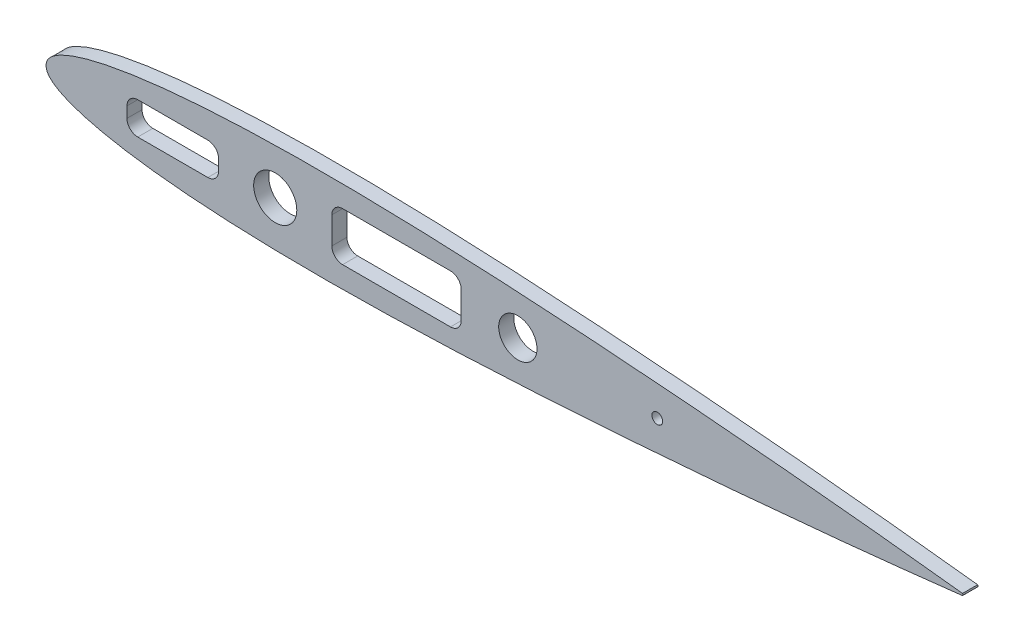
SolidWorks part; units mm, degrees
material "Фанера"
ref_plane "Front Plane" through (0, 0, 0) normal (0, 0, 1) x (1, 0, 0)
ref_plane "Top Plane" through (0, 0, 0) normal (0, 1, 0) x (1, 0, 0)
ref_plane "Right Plane" through (0, 0, 0) normal (1, 0, 0) x (0, 0, -1)
curve "Кривая1"
  spline degree 3 poles (110, 0, 0) (110.0276, -0.2367, 0) (110.0855, -0.7342, 0) (110.5302, -1.4271, 0) (111.1963, -2.0786, 0) (112.1098, -2.7013, 0) (113.2568, -3.2993, 0) (114.6379, -3.8731, 0) (116.2477, -4.4214, 0) (118.0813, -4.9426, 0) (120.1331, -5.4348, 0) (122.3972, -5.8961, 0) (124.8672, -6.3247, 0) (127.537, -6.7187, 0) (130.3997, -7.0764, 0) (133.4488, -7.3965, 0) (136.6771, -7.6776, 0) (140.0777, -7.9187, 0) (143.6433, -8.119, 0) (147.3662, -8.278, 0) (151.2389, -8.3955, 0) (155.2534, -8.4715, 0) (159.4016, -8.5065, 0) (163.6751, -8.501, 0) (168.0653, -8.456, 0) (172.5632, -8.3725, 0) (177.1595, -8.252, 0) (181.8446, -8.096, 0) (186.6087, -7.9062, 0) (191.4413, -7.6846, 0) (196.3316, -7.4331, 0) (201.2684, -7.1538, 0) (206.2396, -6.8489, 0) (211.233, -6.5205, 0) (216.2352, -6.1709, 0) (221.2323, -5.8022, 0) (226.2093, -5.417, 0) (231.1504, -5.0174, 0) (236.0382, -4.6058, 0) (240.8542, -4.1849, 0) (245.5777, -3.7574, 0) (250.1862, -3.3262, 0) (254.6542, -2.8948, 0) (258.9526, -2.4672, 0) (263.0477, -2.0479, 0) (266.899, -1.6426, 0) (270.4558, -1.2586, 0) (273.6512, -0.9053, 0) (276.3854, -0.5964, 0) (278.4526, -0.359, 0) (279.592, -0.2261, 0) (280, -0.1785, 0) knots 0 0 0 0 0.004099 0.008615 0.013935 0.020278 0.027753 0.03641 0.046266 0.05732 0.069559 0.082963 0.097507 0.113164 0.129903 0.14769 0.166492 0.186272 0.206992 0.228612 0.251092 0.274389 0.298458 0.323254 0.348728 0.37483 0.401509 0.42871 0.456376 0.484448 0.512864 0.541558 0.570462 0.599504 0.628607 0.65769 0.686667 0.715445 0.743924 0.771995 0.79954 0.826428 0.852512 0.877624 0.901571 0.924121 0.944989 0.963804 0.980044 0.992855 1 1 1 1
curve "Кривая2"
  spline degree 3 poles (280, 0.1785, 0) (279.592, 0.2261, 0) (278.4526, 0.359, 0) (276.3854, 0.5964, 0) (273.6512, 0.9053, 0) (270.4558, 1.2586, 0) (266.899, 1.6426, 0) (263.0477, 2.0479, 0) (258.9526, 2.4672, 0) (254.6542, 2.8948, 0) (250.1862, 3.3262, 0) (245.5777, 3.7574, 0) (240.8542, 4.1849, 0) (236.0382, 4.6058, 0) (231.1504, 5.0174, 0) (226.2093, 5.417, 0) (221.2323, 5.8022, 0) (216.2352, 6.1709, 0) (211.233, 6.5205, 0) (206.2396, 6.8489, 0) (201.2684, 7.1538, 0) (196.3316, 7.4331, 0) (191.4413, 7.6846, 0) (186.6087, 7.9062, 0) (181.8446, 8.096, 0) (177.1595, 8.252, 0) (172.5632, 8.3725, 0) (168.0653, 8.456, 0) (163.6751, 8.501, 0) (159.4016, 8.5065, 0) (155.2534, 8.4715, 0) (151.2389, 8.3955, 0) (147.3662, 8.278, 0) (143.6433, 8.119, 0) (140.0777, 7.9187, 0) (136.6771, 7.6776, 0) (133.4488, 7.3965, 0) (130.3997, 7.0764, 0) (127.537, 6.7187, 0) (124.8672, 6.3247, 0) (122.3972, 5.8961, 0) (120.1331, 5.4348, 0) (118.0813, 4.9426, 0) (116.2477, 4.4214, 0) (114.6379, 3.8731, 0) (113.2568, 3.2993, 0) (112.1098, 2.7013, 0) (111.1963, 2.0786, 0) (110.5302, 1.4271, 0) (110.0855, 0.7342, 0) (110.0276, 0.2367, 0) (110, 0, 0) knots 0 0 0 0 0.007145 0.019956 0.036196 0.055011 0.075879 0.098429 0.122376 0.147488 0.173572 0.20046 0.228005 0.256076 0.284555 0.313333 0.34231 0.371393 0.400496 0.429538 0.458442 0.487136 0.515552 0.543624 0.57129 0.598491 0.62517 0.651272 0.676746 0.701542 0.725611 0.748908 0.771388 0.793008 0.813728 0.833508 0.85231 0.870097 0.886836 0.902493 0.917037 0.930441 0.94268 0.953734 0.96359 0.972247 0.979722 0.986065 0.991385 0.995901 1 1 1 1
sketch "Эскиз1" plane through (0, 0, 0) normal (0, 0, 1) x (1, 0, 0)
  line L0 (105.1708, 0) -> (280.7263, 0) construction
  line L1 (280.0739, 0) -> (280.0739, 24.3846) construction
  line L2 (110, -5.3315) -> (110, 17.5304) construction
  line L3 (152.5185, 18.8331) -> (152.5185, -21.3473) construction
  line L4 (223.3826, 13.2402) -> (223.3826, -18.4275) construction
  line L5 (217.7476, 6.0581) -> (217.7476, -6.0581)
  line L6 (127.0185, -3) -> (140.0185, -3)
  line L7 (125.0185, -1) -> (125.0185, 1)
  line L8 (127.0185, 3) -> (140.0185, 3)
  line L9 (142.0185, -1) -> (142.0185, 1)
  line L10 (125.0185, -3) -> (142.0185, 3) construction
  line L11 (125.0185, 3) -> (142.0185, -3) construction
  line L12 (165.0185, -4.5) -> (185.0185, -4.5)
  line L13 (163.0185, -2.5) -> (163.0185, 2.5)
  line L14 (165.0185, 4.5) -> (185.0185, 4.5)
  line L15 (187.0185, -2.5) -> (187.0185, 2.5)
  line L16 (163.0185, -4.5) -> (187.0185, 4.5) construction
  line L17 (163.0185, 4.5) -> (187.0185, -4.5) construction
  arc A0 (280, 0.1785) -> (280, -0.1785) centre (279.8215, 0) cw
  circle A1 centre (152.5185, 0) radius 4
  circle A2 centre (197.5185, 0) radius 3.55
  arc A3 (185.0185, 4.5) -> (187.0185, 2.5) centre (185.0185, 2.5) cw
  arc A4 (185.0185, -4.5) -> (187.0185, -2.5) centre (185.0185, -2.5) ccw
  arc A5 (165.0185, -4.5) -> (163.0185, -2.5) centre (165.0185, -2.5) cw
  arc A6 (163.0185, 2.5) -> (165.0185, 4.5) centre (165.0185, 2.5) cw
  arc A7 (125.0185, 1) -> (127.0185, 3) centre (127.0185, 1) cw
  arc A8 (127.0185, -3) -> (125.0185, -1) centre (127.0185, -1) cw
  arc A9 (140.0185, -3) -> (142.0185, -1) centre (140.0185, -1) ccw
  arc A10 (140.0185, 3) -> (142.0185, 1) centre (140.0185, 1) cw
  arc A11 (223.3826, 5.635) -> (223.3826, -5.635) centre (223.3826, 0) ccw
  circle A12 centre (223.3826, 0) radius 1
  spline S0 degree 3 poles (-1802.3351, -584.8827) (164.5267, 33.7772) (105.6543, 6.1699) (110.5302, -1.4271) (111.1963, -2.0786) (112.1098, -2.7013) (113.2568, -3.2993) (114.6379, -3.8731) (116.2477, -4.4214) (118.0813, -4.9426) (120.1331, -5.4348) (122.3972, -5.8961) (124.8672, -6.3247) (127.537, -6.7187) (130.3997, -7.0764) (133.4488, -7.3965) (136.6771, -7.6776) (140.0777, -7.9187) (143.6433, -8.119) (147.3662, -8.278) (151.2389, -8.3955) (155.2534, -8.4715) (159.4016, -8.5065) (163.6751, -8.501) (168.0653, -8.456) (172.5632, -8.3725) (177.1595, -8.252) (181.8446, -8.096) (186.6087, -7.9062) (191.4413, -7.6846) (196.3316, -7.4331) (201.2684, -7.1538) (206.2396, -6.8489) (211.233, -6.5205) (216.2352, -6.1709) (221.2323, -5.8022) (226.2093, -5.417) (231.1504, -5.0174) (236.0382, -4.6058) (240.8542, -4.1849) (247.0711, -3.6222) (253.1161, -3.0479) (258.9526, -2.4672) (263.0477, -2.0479) (266.899, -1.6426) (270.4558, -1.2586) (273.6512, -0.9053) (276.3854, -0.5964) (359.5279, 8.955) (440.5611, 28.5776) (751.5392, -1938.3855) knots -0.13886 -0.13886 -0.13886 -0.13886 0.004099 0.008615 0.013935 0.020278 0.027753 0.03641 0.046266 0.05732 0.069559 0.082963 0.097507 0.113164 0.129903 0.14769 0.166492 0.186272 0.206992 0.228612 0.251092 0.274389 0.298458 0.323254 0.348728 0.37483 0.401509 0.42871 0.456376 0.484448 0.512864 0.541558 0.570462 0.599504 0.628607 0.65769 0.686667 0.715445 0.743924 0.771995 0.79954 0.852512 0.877624 0.901571 0.924121 0.944989 0.963804 0.980044 0.992855 2.419626 2.419626 2.419626 2.419626 only from (110, 0) to (280, -0.1785) construction
  spline S1 degree 3 poles (751.5383, 1938.3796) (440.561, -28.5775) (359.5279, -8.955) (276.3854, 0.5964) (273.6512, 0.9053) (270.4558, 1.2586) (266.899, 1.6426) (263.0477, 2.0479) (258.9526, 2.4672) (253.1161, 3.0479) (247.0711, 3.6222) (240.8542, 4.1849) (236.0382, 4.6058) (231.1504, 5.0174) (226.2093, 5.417) (221.2323, 5.8022) (216.2352, 6.1709) (211.233, 6.5205) (206.2396, 6.8489) (201.2684, 7.1538) (196.3316, 7.4331) (191.4413, 7.6846) (186.6087, 7.9062) (181.8446, 8.096) (177.1595, 8.252) (172.5632, 8.3725) (168.0653, 8.456) (163.6751, 8.501) (159.4016, 8.5065) (155.2534, 8.4715) (151.2389, 8.3955) (147.3662, 8.278) (143.6433, 8.119) (140.0777, 7.9187) (136.6771, 7.6776) (133.4488, 7.3965) (130.3997, 7.0764) (127.537, 6.7187) (124.8672, 6.3247) (122.3972, 5.8961) (120.1331, 5.4348) (118.0813, 4.9426) (116.2477, 4.4214) (114.6379, 3.8731) (113.2568, 3.2993) (112.1098, 2.7013) (111.1963, 2.0786) (110.5302, 1.4271) (105.6546, -6.1694) (164.5198, -33.7739) (-1801.974, 584.7691) knots -1.419625 -1.419625 -1.419625 -1.419625 0.007145 0.019956 0.036196 0.055011 0.075879 0.098429 0.122376 0.147488 0.20046 0.228005 0.256076 0.284555 0.313333 0.34231 0.371393 0.400496 0.429538 0.458442 0.487136 0.515552 0.543624 0.57129 0.598491 0.62517 0.651272 0.676746 0.701542 0.725611 0.748908 0.771388 0.793008 0.813728 0.833508 0.85231 0.870097 0.886836 0.902493 0.917037 0.930441 0.94268 0.953734 0.96359 0.972247 0.979722 0.986065 0.991385 0.995901 1.138851 1.138851 1.138851 1.138851 only from (280, 0.1785) to (110, 0) construction
  spline S2 degree 3 poles (110, 0) (110.0276, -0.2367) (110.0855, -0.7342) (110.5302, -1.4271) (111.1963, -2.0786) (112.1098, -2.7013) (113.2568, -3.2993) (114.6379, -3.8731) (116.2477, -4.4214) (118.0813, -4.9426) (120.1331, -5.4348) (122.3972, -5.8961) (124.8672, -6.3247) (127.537, -6.7187) (130.3997, -7.0764) (133.4488, -7.3965) (136.6771, -7.6776) (140.0777, -7.9187) (143.6433, -8.119) (147.3662, -8.278) (151.2389, -8.3955) (155.2534, -8.4715) (159.4016, -8.5065) (163.6751, -8.501) (168.0653, -8.456) (172.5632, -8.3725) (177.1595, -8.252) (181.8446, -8.096) (186.6087, -7.9062) (191.4413, -7.6846) (196.3316, -7.4331) (201.2684, -7.1538) (206.2396, -6.8489) (211.233, -6.5205) (216.2352, -6.1709) (221.2323, -5.8022) (226.2093, -5.417) (231.1504, -5.0174) (236.0382, -4.6058) (240.8542, -4.1849) (247.0711, -3.6222) (253.1161, -3.0479) (258.9526, -2.4672) (263.0477, -2.0479) (266.899, -1.6426) (270.4558, -1.2586) (273.6512, -0.9053) (276.3854, -0.5964) (278.4526, -0.359) (279.592, -0.2261) (280, -0.1785) knots 0 0 0 0 0.004099 0.008615 0.013935 0.020278 0.027753 0.03641 0.046266 0.05732 0.069559 0.082963 0.097507 0.113164 0.129903 0.14769 0.166492 0.186272 0.206992 0.228612 0.251092 0.274389 0.298458 0.323254 0.348728 0.37483 0.401509 0.42871 0.456376 0.484448 0.512864 0.541558 0.570462 0.599504 0.628607 0.65769 0.686667 0.715445 0.743924 0.771995 0.79954 0.852512 0.877624 0.901571 0.924121 0.944989 0.963804 0.980044 0.992855 1 1 1 1
  spline S3 degree 3 poles (280, 0.1785) (279.592, 0.2261) (278.4526, 0.359) (276.3854, 0.5964) (273.6512, 0.9053) (270.4558, 1.2586) (266.899, 1.6426) (263.0477, 2.0479) (258.9526, 2.4672) (253.1161, 3.0479) (247.0711, 3.6222) (240.8542, 4.1849) (236.0382, 4.6058) (231.1504, 5.0174) (226.2093, 5.417) (221.2323, 5.8022) (216.2352, 6.1709) (211.233, 6.5205) (206.2396, 6.8489) (201.2684, 7.1538) (196.3316, 7.4331) (191.4413, 7.6846) (186.6087, 7.9062) (181.8446, 8.096) (177.1595, 8.252) (172.5632, 8.3725) (168.0653, 8.456) (163.6751, 8.501) (159.4016, 8.5065) (155.2534, 8.4715) (151.2389, 8.3955) (147.3662, 8.278) (143.6433, 8.119) (140.0777, 7.9187) (136.6771, 7.6776) (133.4488, 7.3965) (130.3997, 7.0764) (127.537, 6.7187) (124.8672, 6.3247) (122.3972, 5.8961) (120.1331, 5.4348) (118.0813, 4.9426) (116.2477, 4.4214) (114.6379, 3.8731) (113.2568, 3.2993) (112.1098, 2.7013) (111.1963, 2.0786) (110.5302, 1.4271) (110.0855, 0.7342) (110.0276, 0.2367) (110, 0) knots 0 0 0 0 0.007145 0.019956 0.036196 0.055011 0.075879 0.098429 0.122376 0.147488 0.20046 0.228005 0.256076 0.284555 0.313333 0.34231 0.371393 0.400496 0.429538 0.458442 0.487136 0.515552 0.543624 0.57129 0.598491 0.62517 0.651272 0.676746 0.701542 0.725611 0.748908 0.771388 0.793008 0.813728 0.833508 0.85231 0.870097 0.886836 0.902493 0.917037 0.930441 0.94268 0.953734 0.96359 0.972247 0.979722 0.986065 0.991385 0.995901 1 1 1 1
  point P19 (175.0185, 0)
  point P22 (133.5185, 0)
  point P31 (223.3826, -5.635)
  point P54 (223.3826, 5.635)
  point P55 (223.3826, -5.635)
  point P56 (223.3826, 5.635)
  dimension "D1" = 0.2524
  dimension "D3" = 8
  dimension "D13" = 2
  dimension "D14" = 5.635
  dimension "D15" = 2
  dimension "D16" = 7.1
  dimension "D2" = 170.0739
  dimension "D4" = 42.5185
  dimension "D5" = 56.6913
  dimension "D6" = 45
  dimension "D7" = 6
  dimension "D8" = 17
  dimension "D9" = 19
  dimension "D10" = 22.5
  dimension "D11" = 9
  dimension "D12" = 24
extrude "Бобышка-Вытянуть1" add sketch "Эскиз1" along normal mid plane 2.8 contours A11 S3 S2 L8 A10 L9 A9 L6 A8 L7 A7 L13 A6 L14 A3 L15 A4 L12 A5 A1 A2 | A0 S3 A11 S2 A12 | L5 S2 A11 | A11 S3 L5
equation "\"D4@Эскиз1\"=\"D2@Эскиз1\"/4"
equation "\"D5@Эскиз1\"=\"D2@Эскиз1\"/3"
equation "\"D10@Эскиз1\"=\"D6@Эскиз1\"/2"
